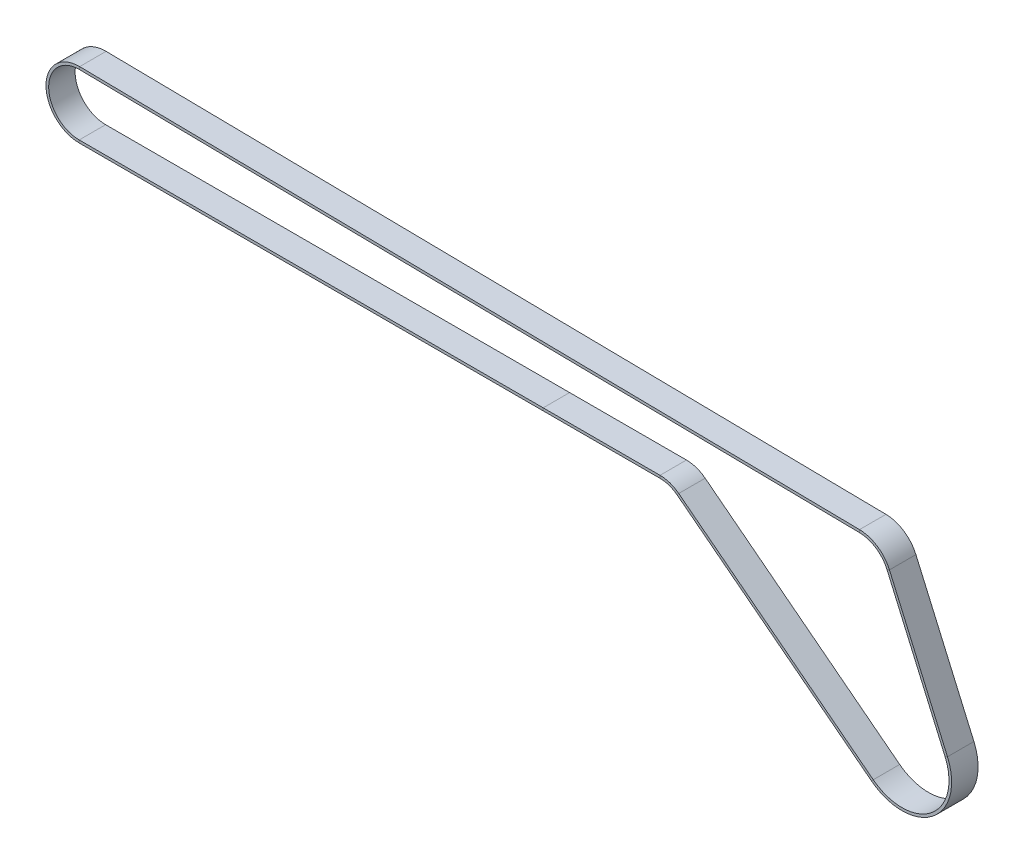
SolidWorks part; units mm, degrees
material "矽膠"
ref_plane "前基準面" through (0, 0, 0) normal (0, 0, 1) x (1, 0, 0)
ref_plane "上基準面" through (0, 0, 0) normal (0, 1, 0) x (1, 0, 0)
ref_plane "右基準面" through (0, 0, 0) normal (1, 0, 0) x (0, 0, -1)
sketch "草圖2" plane through (0, 0, 0) normal (0, 0, 1) x (1, 0, 0)
  line L0 (126.8338, -1.9208) -> (127.8338, -1.9208) construction
  line L1 (126.8338, -1.9208) -> (126.8338, -0.9208) construction
  line L2 (152.0034, -38.2428) -> (130.0568, 12.0069)
  line L3 (119.6312, 18.9359) -> (-175.3393, 23.1088)
  line L4 (-175.5028, 0) -> (44.1923, 0)
  line L5 (51.2672, -2.4191) -> (124.8463, -59.3989)
  line L6 (187.726, 0) -> (-187.726, 0) construction
  arc A0 (124.8463, -59.3989) -> (152.0034, -38.2428) centre (135.7234, -45.3531) ccw
  arc A1 (130.0568, 12.0069) -> (119.6312, 18.9359) centre (119.4677, 7.3821) ccw
  arc A2 (-175.3393, 23.1088) -> (-175.5028, 0) centre (-175.5028, 11.555) ccw
  arc A3 (44.1923, 0) -> (51.2672, -2.4191) centre (44.1923, -11.555) cw
sketch "草圖4" plane through (0, 0, 0) normal (1, 0, 0) x (0, 0, -1)
  line L1 (-5, 0) -> (5, 0)
  line L2 (-5, 0) -> (-5, -1)
  line L3 (-5, -1) -> (5, -1)
  line L4 (5, 0) -> (5, -1)
  dimension "D1" = 10
  dimension "D2" = 1
sweep "掃出1" add profiles "草圖4" path "草圖2"
